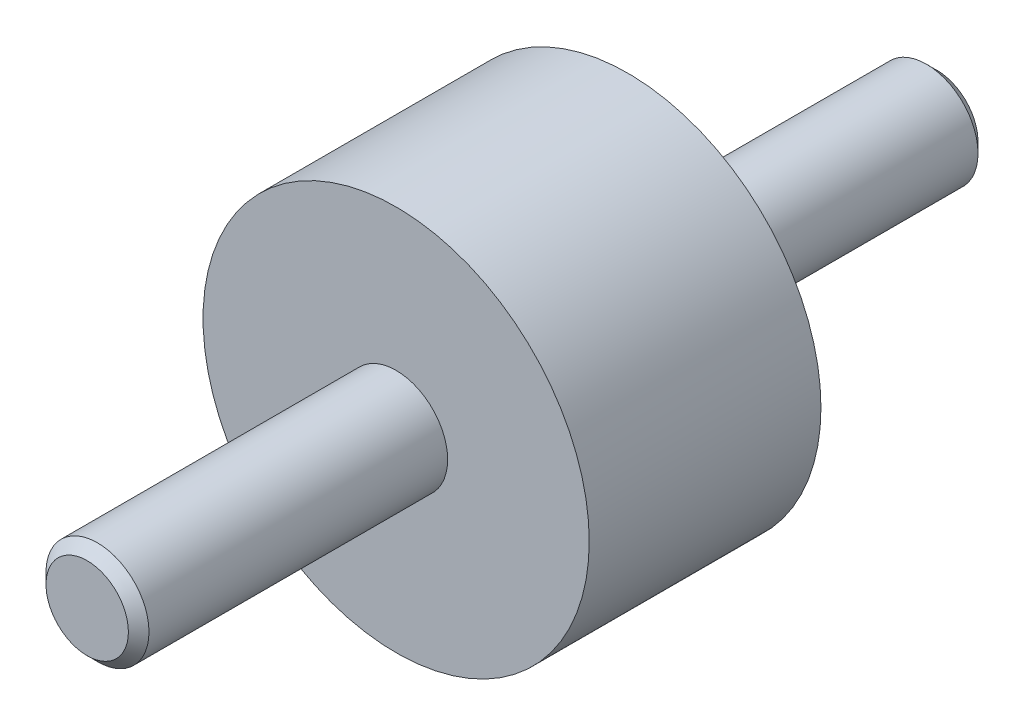
SolidWorks part; units mm, degrees
ref_plane "Plan de face" through (0, 0, 0) normal (0, 0, 1) x (1, 0, 0)
ref_plane "Plan de dessus" through (0, 0, 0) normal (0, 1, 0) x (1, 0, 0)
ref_plane "Plan de droite" through (0, 0, 0) normal (1, 0, 0) x (0, 0, -1)
sketch "Esquisse1" plane through (0, 0, 0) normal (0, 0, 1) x (1, 0, 0)
  circle A0 centre (0, 0) radius 7.5
  dimension "D1" = 15
extrude "Extrusion1" add sketch "Esquisse1" along normal blind 9
sketch "Esquisse2" plane through (0, 0, 9) normal (0, 0, 1) x (1, 0, 0)
  circle A0 centre (0, 0) radius 2
  dimension "D1" = 4
extrude "Extrusion2" add sketch "Esquisse2" along normal blind 12
cosmetic thread "Représentation de filetage1" parameters "D1"=12, "D2"=3.2
sketch "Esquisse3" plane through (0, 0, 0) normal (0, 0, -1) x (-1, 0, 0)
  circle A0 centre (0, 0) radius 2
  dimension "D1" = 4
extrude "Extrusion3" add sketch "Esquisse3" along normal blind 12
cosmetic thread "Représentation de filetage2" parameters "D1"=12, "D2"=3.2
chamfer "Chanfrein1" distance 0.4 angle 45 2 edges at (-2, 0, -12) (2, 0, 21)
